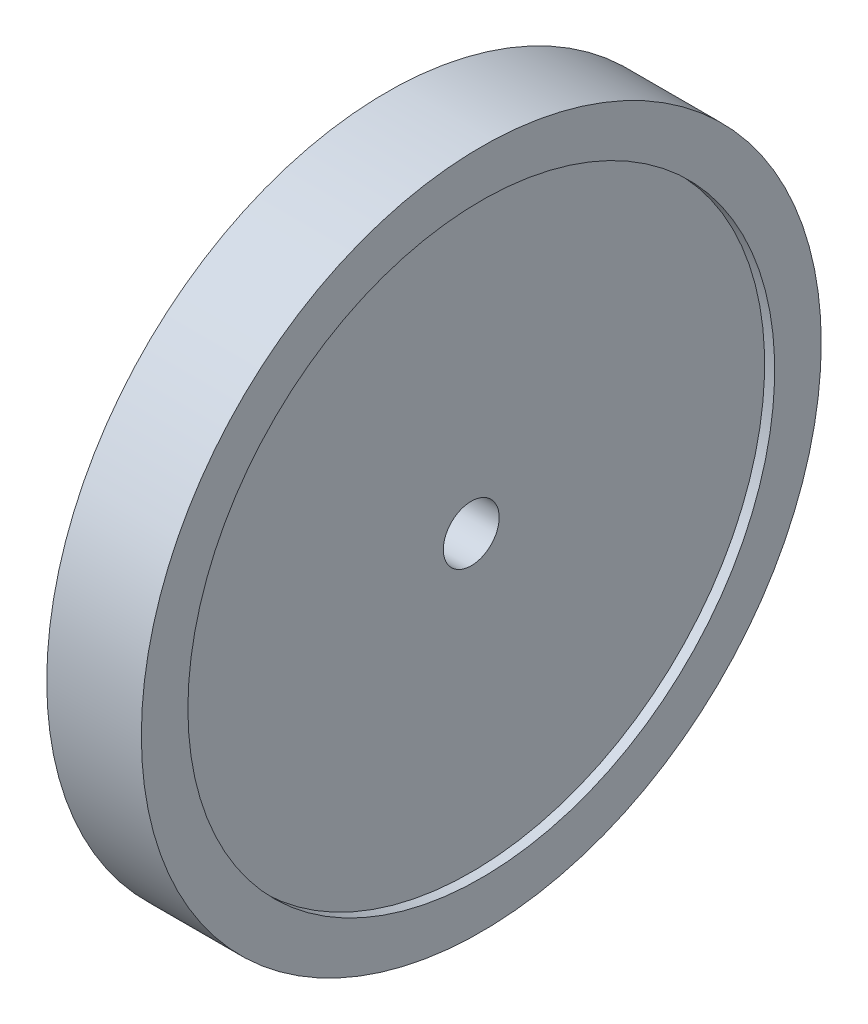
SolidWorks part; units mm, degrees
ref_plane "Plan de face" through (0, 0, 0) normal (0, 0, 1) x (1, 0, 0)
ref_plane "Plan de dessus" through (0, 0, 0) normal (0, 1, 0) x (1, 0, 0)
ref_plane "Plan de droite" through (0, 0, 0) normal (1, 0, 0) x (0, 0, -1)
sketch "Esquisse1" plane through (0, 0, 0) normal (0, 0, 1) x (1, 0, 0)
  line L0 (-4, 31.5125) -> (-5.08, 31.5125)
  line L1 (-4, 0) -> (4, 0)
  line L2 (-4, 0) -> (-4, 31.5125)
  line L4 (4, 0) -> (4, 31.5125)
  line L5 (-5.08, 31.5125) -> (-5.08, 36.5125)
  line L6 (-5.08, 36.5125) -> (5.08, 36.5125)
  line L7 (5.08, 36.5125) -> (5.08, 31.5125)
  line L8 (5.08, 31.5125) -> (4, 31.5125)
  line L9 (0, 0) -> (0, 79.5434) construction
  dimension "D1" = 10.16
  dimension "D2" = 5.08
  dimension "D3" = 4
  dimension "D4" = 8
  dimension "D5" = 36.5125
  dimension "D6" = 5
revolve "Révolution1" add sketch "Esquisse1" angle 360 about L1
sketch "Esquisse2" plane through (4, 0, 0) normal (1, 0, 0) x (0, 0, -1)
  circle A0 centre (0, 0) radius 3
  dimension "D1" = 6
extrude "Enlèv. mat.-Extru.2" cut sketch "Esquisse2" against normal through all
equation "\"D2@Esquisse1\"=\"D1@Esquisse1\"/2"
equation "\"D4@Esquisse1\"=\"D3@Esquisse1\"+\"D3@Esquisse1\""
